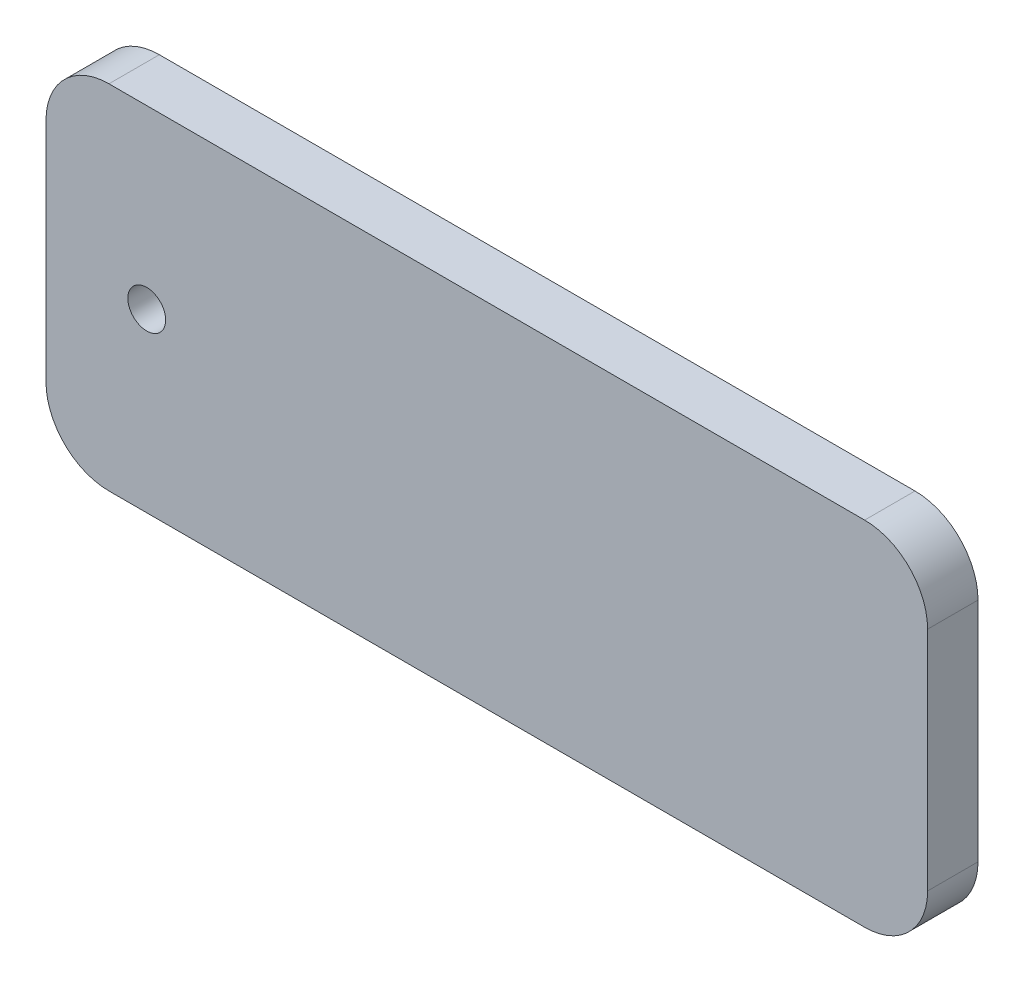
SolidWorks part; units mm, degrees
ref_plane "Front Plane" through (0, 0, 0) normal (0, 0, 1) x (1, 0, 0)
ref_plane "Top Plane" through (0, 0, 0) normal (0, 1, 0) x (1, 0, 0)
ref_plane "Right Plane" through (0, 0, 0) normal (1, 0, 0) x (0, 0, -1)
sketch "Sketch1" plane through (0, 0, 0) normal (0, 0, 1) x (1, 0, 0)
  line L0 (0, 14) -> (23.5043, 14) construction
  line L1 (5, 0) -> (65, 0)
  line L2 (0, 5) -> (0, 23)
  line L3 (5, 28) -> (65, 28)
  line L4 (70, 5) -> (70, 23)
  circle A0 centre (8, 14) radius 1.5
  arc A1 (5, 0) -> (0, 5) centre (5, 5) cw
  arc A2 (65, 0) -> (70, 5) centre (65, 5) ccw
  arc A3 (65, 28) -> (70, 23) centre (65, 23) cw
  arc A4 (0, 23) -> (5, 28) centre (5, 23) cw
  point P11 (0, 0)
  point P14 (70, 0)
  point P17 (70, 28)
  point P20 (0, 28)
  dimension "D3" = 3
  dimension "D5" = 5
  dimension "D1" = 28
  dimension "D2" = 70
  dimension "D4" = 8
extrude "Boss-Extrude1" add sketch "Sketch1" along normal blind 4
